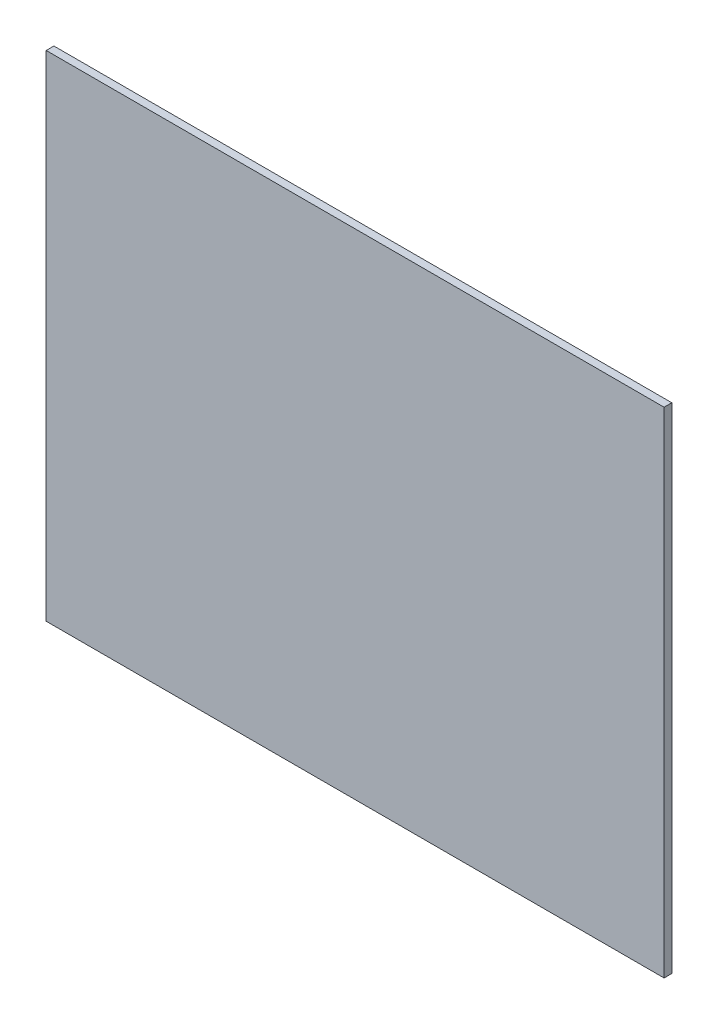
SolidWorks part; units mm, degrees
ref_plane "Front Plane" through (0, 0, 0) normal (0, 0, 1) x (1, 0, 0)
ref_plane "Top Plane" through (0, 0, 0) normal (0, 1, 0) x (1, 0, 0)
ref_plane "Right Plane" through (0, 0, 0) normal (1, 0, 0) x (0, 0, -1)
sketch "Sketch1" plane through (0, 0, 0) normal (0, 0, 1) x (1, 0, 0)
  line L1 (0, 0) -> (254, 0)
  line L2 (0, 0) -> (0, 203.2)
  line L3 (0, 203.2) -> (254, 203.2)
  line L4 (254, 0) -> (254, 203.2)
  dimension "D1" = 254
  dimension "D2" = 203.2
extrude "Boss-Extrude2" add sketch "Sketch1" along normal blind 3.175 contours L3 L4 L1 L2
